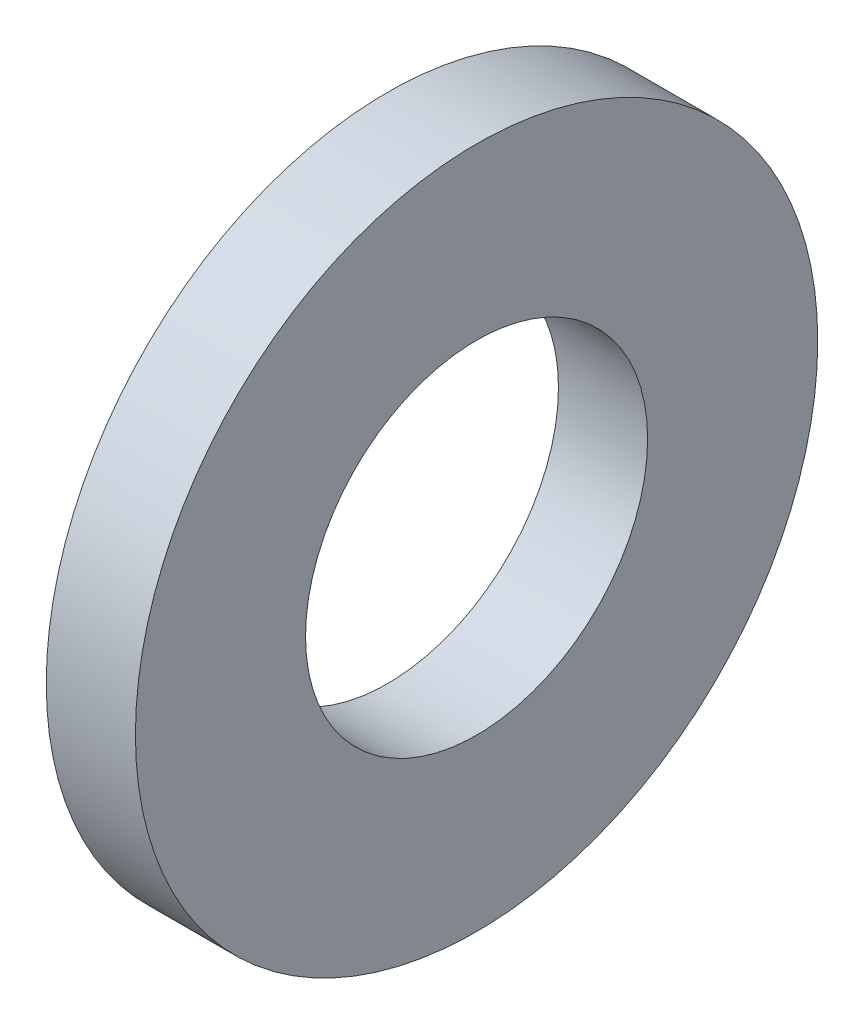
SolidWorks part; units mm, degrees
material "Chrome Stainless Steel"
ref_plane "Front Plane" through (0, 0, 0) normal (0, 0, 1) x (1, 0, 0)
ref_plane "Top Plane" through (0, 0, 0) normal (0, 1, 0) x (1, 0, 0)
ref_plane "Right Plane" through (0, 0, 0) normal (1, 0, 0) x (0, 0, -1)
ref_plane "Plane1" through (0, 0, 0) normal (0, 0, -1) x (-1, 0, 0)
sketch "Sketch1" plane through (0, 0, 0) normal (0, 0, -1) x (-1, 0, 0)
  line L0 (1.2446, 4.7625) -> (0, 4.7625)
  line L1 (0, 4.7625) -> (0, 2.3876)
  line L2 (0, 2.3876) -> (1.2446, 2.3876)
  line L3 (1.2446, 2.3876) -> (1.2446, 4.7625)
  line L4 (0, 0) -> (1.2446, 0) construction
revolve "Revolve1" add sketch "Sketch1" angle 360 about L4
